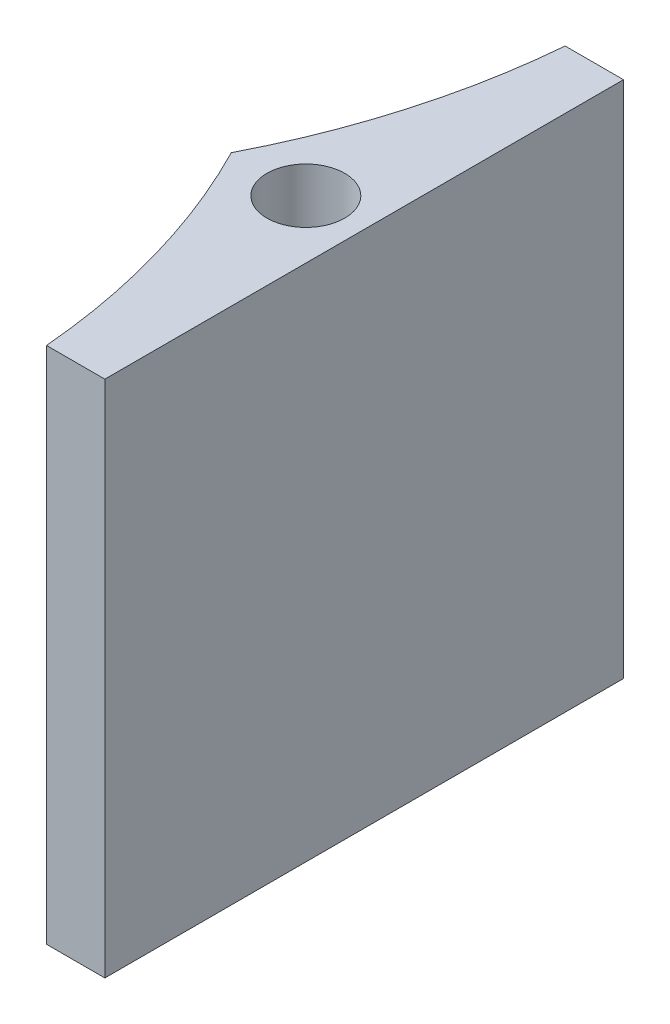
SolidWorks part; units mm, degrees
ref_plane "Front Plane" through (0, 0, 0) normal (0, 0, 1) x (1, 0, 0)
ref_plane "Top Plane" through (0, 0, 0) normal (0, 1, 0) x (1, 0, 0)
ref_plane "Right Plane" through (0, 0, 0) normal (1, 0, 0) x (0, 0, -1)
sketch "Sketch1" plane through (0, 0, 0) normal (0, 1, 0) x (1, 0, 0)
  line L0 (0, -22) -> (0, 22) construction
  line L1 (0, 20) -> (4.5, 20)
  line L3 (0, -20) -> (4.5, -20)
  line L4 (4.5, 20) -> (4.5, -20)
  line L5 (-59.3226, 0) -> (59.3226, 0) construction
  line L6 (54.6736, 0) -> (-53.1857, 0) construction
  circle A0 centre (0, 0) radius 3
  arc A1 (0, 20) -> (-5.7494, 0) centre (-53.6194, 24.5877) cw
  arc A2 (0, -20) -> (-5.7494, 0) centre (-53.6194, -24.5877) ccw
  dimension "D1" = 6
  dimension "D2" = 40
  dimension "D4" = 4.5
extrude "Boss-Extrude1" add sketch "Sketch1" along normal blind 40
